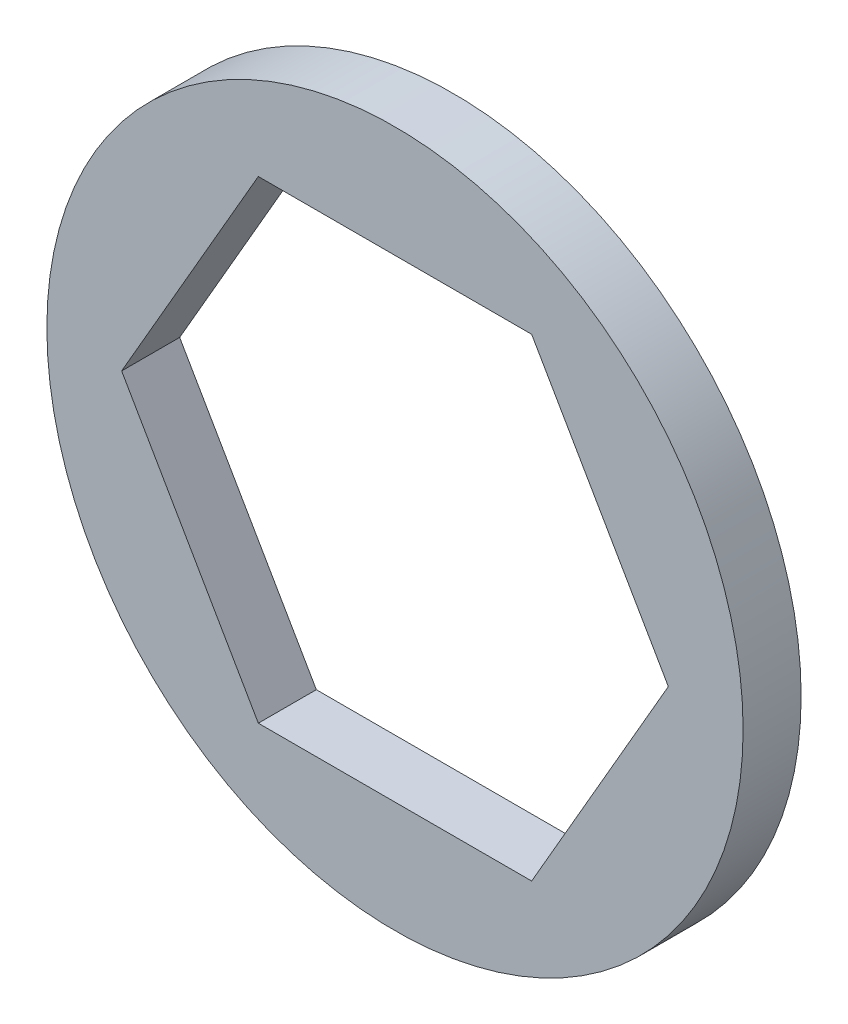
SolidWorks part; units mm, degrees
material "PET"
ref_plane "Front Plane" through (0, 0, 0) normal (0, 0, 1) x (1, 0, 0)
ref_plane "Top Plane" through (0, 0, 0) normal (0, 1, 0) x (1, 0, 0)
ref_plane "Right Plane" through (0, 0, 0) normal (1, 0, 0) x (0, 0, -1)
sketch "Sketch1" plane through (0, 0, 0) normal (0, 0, 1) x (1, 0, 0)
  line L7 (7.479, 0) -> (3.7395, 6.477)
  line L8 (3.7395, 6.477) -> (-3.7395, 6.477)
  line L9 (-3.7395, 6.477) -> (-7.479, 0)
  line L10 (-7.479, 0) -> (-3.7395, -6.477)
  line L11 (-3.7395, -6.477) -> (3.7395, -6.477)
  line L12 (3.7395, -6.477) -> (7.479, 0)
  circle A2 centre (0, 0) radius 6.477 construction
  circle A3 centre (0, 0) radius 9.525
  dimension "D1" = 19.05
  dimension "D2" = 12.954
extrude "Boss-Extrude1" add sketch "Sketch1" along normal mid plane 1.5875
